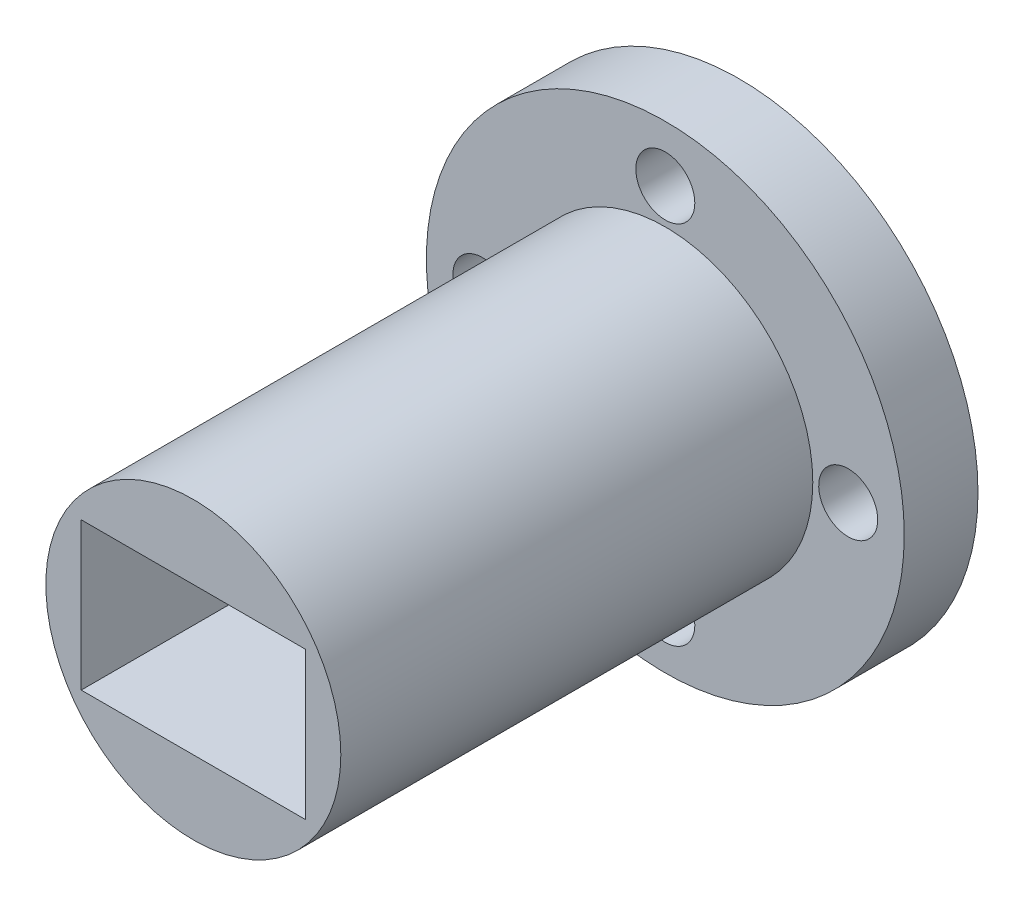
SolidWorks part; units mm, degrees
ref_plane "Front Plane" through (0, 0, 0) normal (0, 0, 1) x (1, 0, 0)
ref_plane "Top Plane" through (0, 0, 0) normal (0, 1, 0) x (1, 0, 0)
ref_plane "Right Plane" through (0, 0, 0) normal (1, 0, 0) x (0, 0, -1)
sketch "Sketch1" plane through (0, 0, 0) normal (0, 0, 1) x (1, 0, 0)
  circle A0 centre (0, 0) radius 10.287
  dimension "D1" = 20.574
extrude "Boss-Extrude1" add sketch "Sketch1" along normal blind 3.175
sketch "Sketch3" plane through (0, 0, 0) normal (0, 0, -1) x (-1, 0, 0)
  circle A0 centre (0, 0) radius 4.064
  dimension "D1" = 8.128
extrude "Cut-Extrude1" cut sketch "Sketch3" against normal blind 2.3813
fillet "Fillet1" radius 1 1 edges at (-4.064, 0, 0)
sketch "Sketch4" plane through (0, 0, 0) normal (0, 0, -1) x (-1, 0, 0)
  circle A0 centre (0, 7.874) radius 1.27
  dimension "D1" = 2.54
  dimension "D2" = 7.874
extrude "Cut-Extrude2" cut sketch "Sketch4" against normal up to next
pattern_circular "CirPattern1" count 4 over 360 about axis through (0, 0, 0) along (0, 0, 1) of "Cut-Extrude2"
sketch "Sketch5" plane through (0, 0, 3.175) normal (0, 0, 1) x (1, 0, 0)
  circle A0 centre (0, 0) radius 6.35
  dimension "D1" = 12.7
extrude "Boss-Extrude2" add sketch "Sketch5" along normal blind 20.32
sketch "Sketch6" plane through (0, 0, 23.495) normal (0, 0, 1) x (1, 0, 0)
  line L1 (4.826, -3.175) -> (-4.826, -3.175)
  line L2 (4.826, -3.175) -> (4.826, 3.175)
  line L3 (4.826, 3.175) -> (-4.826, 3.175)
  line L4 (-4.826, -3.175) -> (-4.826, 3.175)
  line L5 (4.826, -3.175) -> (-4.826, 3.175) construction
  line L6 (4.826, 3.175) -> (-4.826, -3.175) construction
  point P0 (0, 0)
  dimension "D1" = 6.35
  dimension "D2" = 9.652
extrude "Cut-Extrude3" cut sketch "Sketch6" against normal blind 19.05
